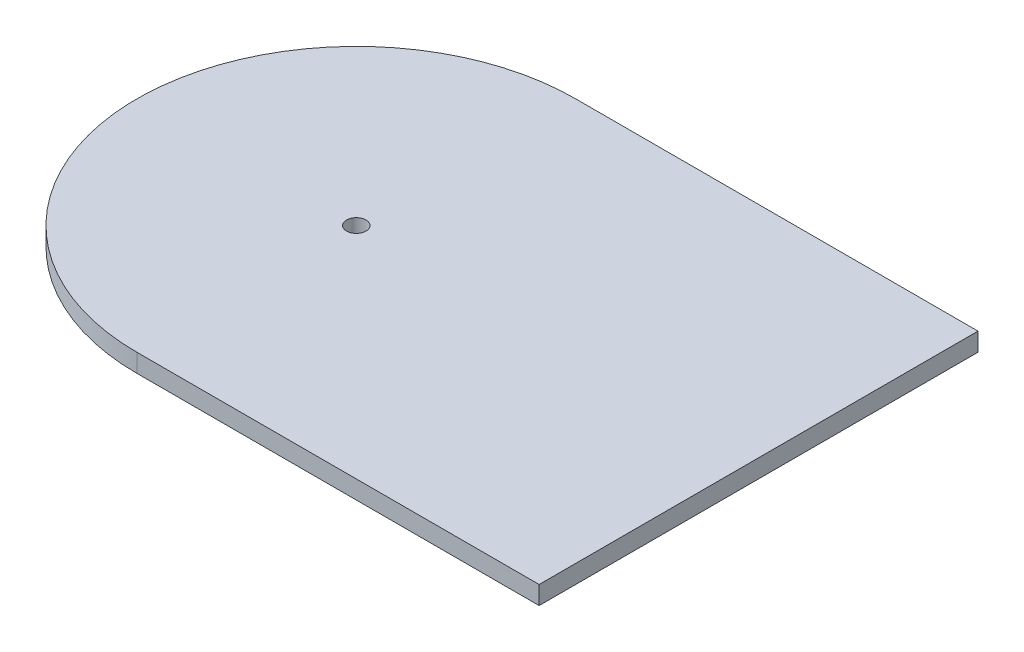
SolidWorks part; units mm, degrees
ref_plane "Front Plane" through (0, 0, 0) normal (0, 0, 1) x (1, 0, 0)
ref_plane "Top Plane" through (0, 0, 0) normal (0, 1, 0) x (1, 0, 0)
ref_plane "Right Plane" through (0, 0, 0) normal (1, 0, 0) x (0, 0, -1)
sketch "Sketch1" plane through (0, 0, 0) normal (0, 1, 0) x (1, 0, 0)
  line L0 (0, -76.2) -> (0, 76.2)
  line L1 (0, -76.2) -> (139.7, -76.2)
  line L2 (0, 76.2) -> (139.7, 76.2)
  line L3 (139.7, -76.2) -> (139.7, 76.2)
  circle A0 centre (0, 0) radius 76.2
  circle A1 centre (0, 0) radius 3.3655
  dimension "D1" = 152.4
  dimension "D2" = 6.731
  dimension "D3" = 139.7
extrude "Boss-Extrude1" add sketch "Sketch1" along normal blind 6.35 contours A1 L0 A0 | A1 L0 A0 | A0 L1 L3 L2
